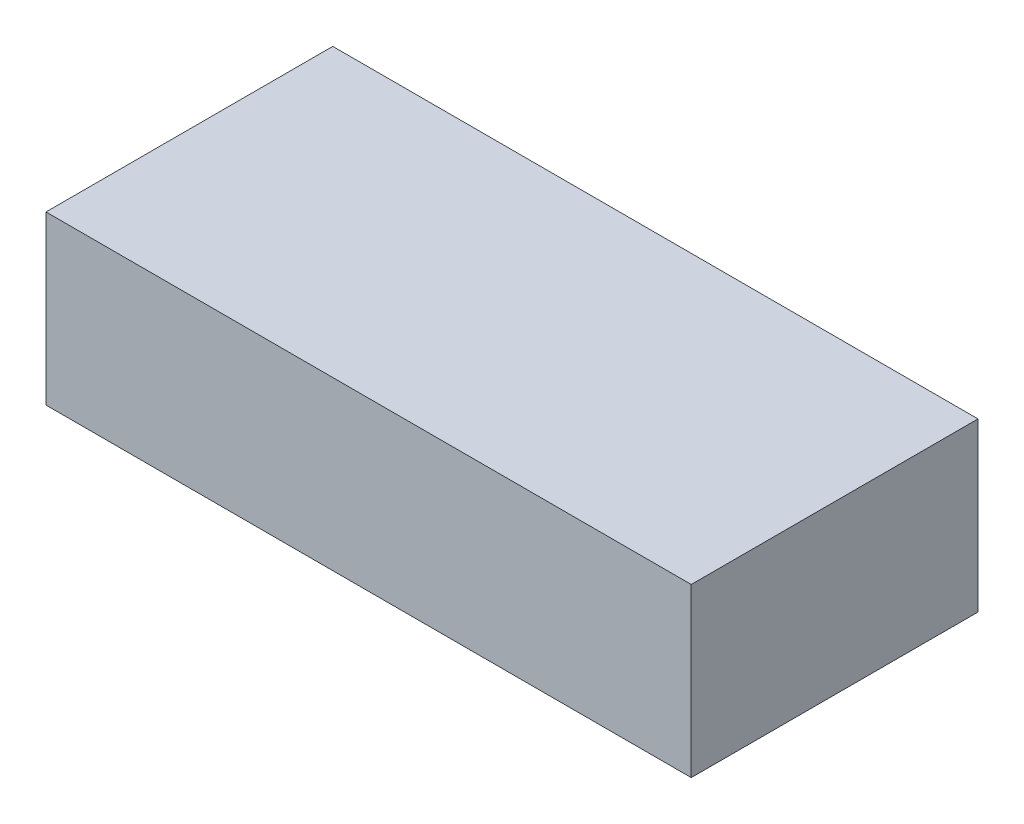
SolidWorks part; units mm, degrees
ref_plane "Front Plane" through (0, 0, 0) normal (0, 0, 1) x (1, 0, 0)
ref_plane "Top Plane" through (0, 0, 0) normal (0, 1, 0) x (1, 0, 0)
ref_plane "Right Plane" through (0, 0, 0) normal (1, 0, 0) x (0, 0, -1)
sketch "Sketch1" plane through (0, 0, 0) normal (0, 1, 0) x (1, 0, 0)
  line L1 (-89.9595, -32.2932) -> (180.0405, -32.2932)
  line L2 (-89.9595, -32.2932) -> (-89.9595, 87.7068)
  line L3 (-89.9595, 87.7068) -> (180.0405, 87.7068)
  line L4 (180.0405, -32.2932) -> (180.0405, 87.7068)
  dimension "D1" = 270
  dimension "D2" = 120
extrude "Boss-Extrude1" add sketch "Sketch1" along normal blind 70 contours L3 L4 L1 L2
